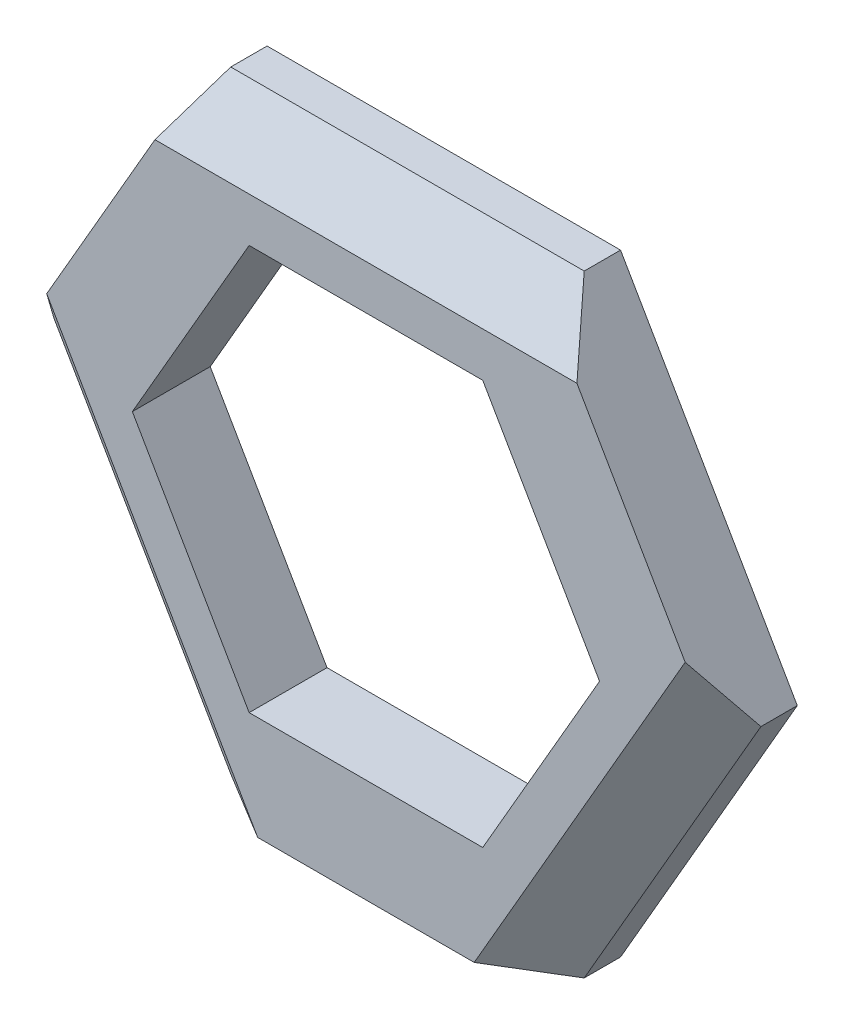
SolidWorks part; units mm, degrees
ref_plane "Front Plane" through (0, 0, 0) normal (0, 0, 1) x (1, 0, 0)
ref_plane "Top Plane" through (0, 0, 0) normal (0, 1, 0) x (1, 0, 0)
ref_plane "Right Plane" through (0, 0, 0) normal (1, 0, 0) x (0, 0, -1)
sketch "Sketch1" plane through (0, 0, 0) normal (0, 0, 1) x (1, 0, 0)
  line L0 (45, 0) -> (22.5, 38.9711)
  line L1 (34.047, 58.9711) -> (-34.047, 58.9711)
  line L2 (-34.047, 58.9711) -> (-68.094, 0)
  line L3 (-68.094, 0) -> (-34.047, -58.9711)
  line L4 (-34.047, -58.9711) -> (34.047, -58.9711)
  line L5 (34.047, -58.9711) -> (68.094, 0)
  line L6 (68.094, 0) -> (34.047, 58.9711)
  line L7 (22.5, 38.9711) -> (-22.5, 38.9711)
  line L8 (-22.5, 38.9711) -> (-45, 0)
  line L9 (-45, 0) -> (-22.5, -38.9711)
  line L10 (-22.5, -38.9711) -> (22.5, -38.9711)
  line L11 (22.5, -38.9711) -> (45, 0)
  circle A0 centre (0, 0) radius 58.9711 construction
  dimension "D1" = 45
  dimension "D2" = 20
extrude "Boss-Extrude1" add sketch "Sketch1" along normal blind 15
chamfer "Chamfer1" distance 8 angle 55 3 edges at (-51.0705, -29.4856, 15) (51.0705, -29.4856, 15) (0, 58.9711, 15)
